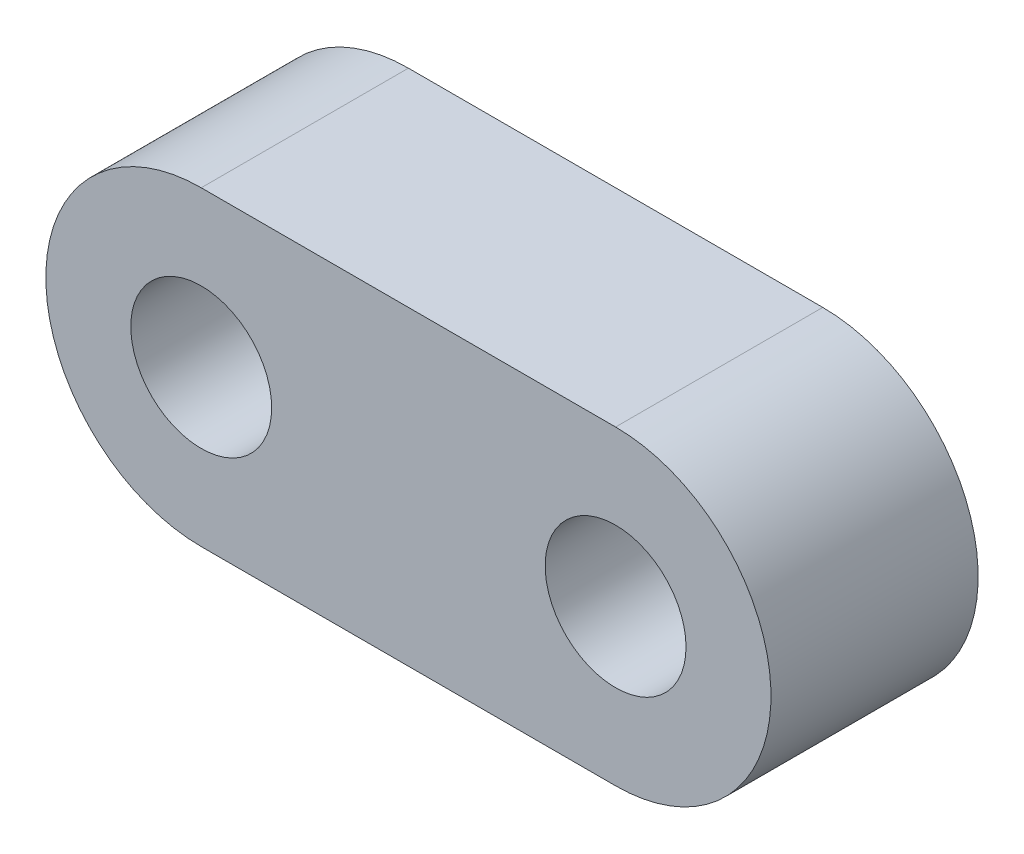
SolidWorks part; units mm, degrees
ref_plane "Front Plane" through (0, 0, 0) normal (0, 0, 1) x (1, 0, 0)
ref_plane "Top Plane" through (0, 0, 0) normal (0, 1, 0) x (1, 0, 0)
ref_plane "Right Plane" through (0, 0, 0) normal (1, 0, 0) x (0, 0, -1)
sketch "Sketch1" plane through (0, 0, 0) normal (0, 0, 1) x (1, 0, 0)
  line L0 (0, 0) -> (12.7, 0) construction
  line L1 (0, 4.7625) -> (12.7, 4.7625)
  line L2 (0, -4.7625) -> (12.7, -4.7625)
  arc A0 (0, 4.7625) -> (0, -4.7625) centre (0, 0) ccw
  arc A1 (12.7, -4.7625) -> (12.7, 4.7625) centre (12.7, 0) ccw
  circle A2 centre (12.7, 0) radius 2.159
  circle A3 centre (0, 0) radius 2.159
  point P3 (6.35, 0)
  dimension "D2" = 9.525
  dimension "D3" = 4.318
  dimension "D1" = 12.7
extrude "Boss-Extrude1" add sketch "Sketch1" along normal blind 6.35
